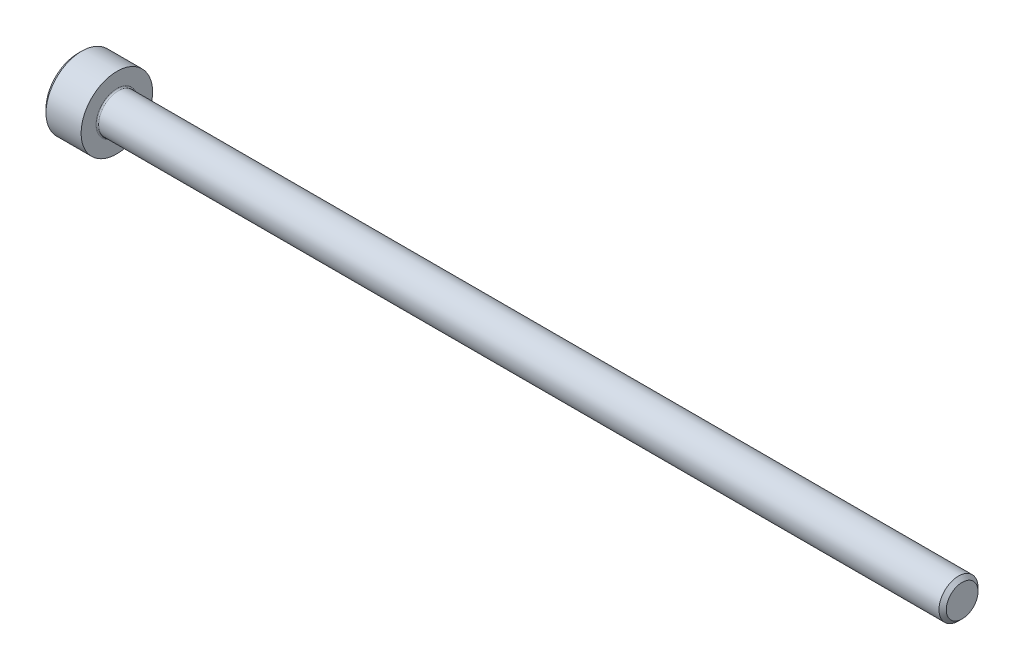
SolidWorks part; units mm, degrees
revolve "Base-Revolve" add sketch "BodySke"
sketch "BodySke" plane through (0, 0, 0) normal (0, 0, 1) x (1, 0, 0)
  line L0 (0, 0) -> (0, 2.45)
  line L1 (0.3, 2.75) -> (3, 2.75)
  line L2 (3, 2.75) -> (3, 1.5)
  line L3 (3, 1.5) -> (67.7195, 1.5)
  line L4 (68, 1.2195) -> (68, 0)
  line L5 (68, 0) -> (0, 0)
  line L6 (-31.75, 0) -> (127, 0) construction
  line L7 (0, 2.45) -> (0.3, 2.75)
  line L8 (68, 1.2195) -> (67.7195, 1.5)
  line L9 (0, -2.45) -> (0.3, -2.75) construction
  line L10 (68, -1.2195) -> (67.7195, -1.5) construction
  line L11 (3.5, 9.525) -> (3.5, 3.175) construction
  line L12 (50, 9.525) -> (50, 3.175) construction
  line L13 (18, 9.525) -> (18, 3.175) construction
  dimension "Diameter" = 3
  dimension "Head_ht" = 3
  dimension "Length" = 65
  dimension "Body_ch_ang" = 45
  dimension "Head_dia" = 5.5
  dimension "Head_ch_ang" = 45
  dimension "Minor_dia" = 2.439
  dimension "Advance" = 0.5
  dimension "Thread_nom" = 18
  dimension "Thread_length" = 50
  dimension "Head_ch_ht" = 0.3
cosmetic thread "ThreadCosmetic" [suppressed]
fillet "Fillet1" radius 0.1 1 edges at (3, 0, 1.5)
ref_plane "Plane1" through (0, 0, 0) normal (0, 0, 1) x (1, 0, 0)
ref_plane "Plane2" through (0, 0, 0) normal (0, 1, 0) x (1, 0, 0)
ref_plane "Plane3" through (0, 0, 0) normal (1, 0, 0) x (0, 0, -1)
sketch "Sketch2" plane through (0, 0, 0) normal (0, 0, 1) x (1, 0, 0)
  line L0 (0, 1.28) -> (1.3, 1.28)
  line L1 (1.3, 1.28) -> (2.039, 0)
  line L2 (-31.75, 0) -> (127, 0) construction
  line L3 (2.039, 0) -> (0, 0)
  line L4 (0, 0) -> (0, 1.28)
  line L5 (0, 2.45) -> (0, -2.45) construction
  line L6 (0, 0) -> (47.625, 0) construction
  line L7 (3, -2.75) -> (3, 2.75) construction
  dimension "D2" = 60
revolve "Hex-PreBroach" cut sketch "Sketch2" angle 360 about L6
sketch "Sketch3" plane through (0, 0, 0) normal (-1, 0, 0) x (0, 0.5, 0.866)
  line L0 (0.739, 1.28) -> (-0.739, 1.28)
  line L1 (-0.739, 1.28) -> (-1.478, 0)
  line L2 (0.739, 1.28) -> (1.478, 0)
  line L3 (0.739, -1.28) -> (1.478, 0)
  line L4 (0.739, -1.28) -> (-0.739, -1.28)
  line L5 (-0.739, -1.28) -> (-1.478, 0)
extrude "Hex" cut sketch "Sketch3" against normal blind 1.3
sketch "Sketch4" plane through (0, 0, 0) normal (-1, 0, 0) x (0, 0, 1)
  line L0 (0, 0) -> (1.4605, 0)
  line L1 (0, 0) -> (6.1484, 3.5498) construction
  line L2 (0, 0) -> (0.7302, 1.2648)
  line L3 (1.2009, 0.3267) -> (1.3933, 0.4378)
  line L4 (0.8834, 0.8767) -> (1.0758, 0.9877)
  arc A0 (1.2009, 0.3267) -> (0.8834, 0.8767) centre (0, 0) ccw
  arc A1 (1.4605, 0) -> (1.3933, 0.4378) centre (0, 0) ccw
  arc A2 (0.7302, 1.2648) -> (1.0758, 0.9877) centre (0, 0) cw
  dimension "D1" = 30
  dimension "D2" = 60
extrude "Spline" [suppressed] cut sketch "Sketch4" against normal blind 1.3
pattern_circular "CirPattern1" [suppressed] count 6 every 60
sketch "Sketch5" plane through (0, 0, 0) normal (0, 0, 1) x (1, 0, 0)
  line L0 (-31.75, 0) -> (127, 0) construction
  line L2 (0, 2.45) -> (0, -2.45) construction
  circle A0 centre (1.2, 0) radius 0.475
  dimension "Drilled_hole_dia" = 0.95
  dimension "Drilled_hole_loc" = 1.2
extrude "Hole" [suppressed] cut sketch "Sketch5" against normal through all and the other way through all
pattern_circular "Drilled-4" [suppressed] count 2 every 60
pattern_circular "Drilled-6" [suppressed] count 3 every 60
sketch "ThdSchSke" plane through (0, 0, 0) normal (0, 0, 1) x (1, 0, 0)
  line L0 (50, -1.2195) -> (49.8036, -1.5)
  line L1 (50, -1.2195) -> (50.1964, -1.5)
  line L2 (50.1964, -1.5) -> (50.1964, -1.875)
  line L3 (-3.175, 0) -> (5.1513, 0) construction
  line L5 (50.1964, -1.875) -> (49.8036, -1.875)
  line L6 (49.8036, -1.875) -> (49.8036, -1.5)
  line L7 (0, 2.45) -> (0, -2.45) construction
revolve "ThreadSchematic" [suppressed] cut sketch "ThdSchSke" angle 360 about L3
pattern_linear "ThdSchPat" [suppressed]
equation "\"D2@Sketch3\" = \"Hex_size@Sketch3\" / 2"
equation "\"D1@Sketch3\" = \"Hex_size@Sketch3\" / 2"
equation "\"D1@Sketch2\" = \"Hex_size@Sketch3\" / 2"
equation "\"D3@Sketch4\" = \"Spline_p_dim@Sketch4\" / 2"
equation "\"Thread_minor@ThreadCosmetic\"  =  \"Minor_dia@BodySke\""
equation "\"D2@CirPattern1\" = 360 / \"Num_teeth@CirPattern1\""
equation "\"Wall_thickness@Sketch2\" = \"Head_ht@BodySke\" - \"Key_eng@Hex\""
equation "\"Thread_length@ThreadCosmetic\" = ((sgn( (\"Length@BodySke\" - \"Advance@BodySke\" ) - \"Thread_nom@BodySke\" )-1)*( (\"Length@BodySke\" - \"Advance@BodySke\" ) - \"Thread_nom@BodySke\" ))/-2+ \"Thread_nom@BodySke\""
equation "\"Thread_minor@ThdSchSke\" = \"Minor_dia@BodySke\""
equation "\"Diameter@ThdSchSke\" = \"Diameter@BodySke\""
equation "\"Overcut@ThdSchSke\" = \"Diameter@BodySke\" * 1.25"
equation "\"Start@ThdSchSke\" = \"Head_ht@BodySke\" + \"Length@BodySke\" - \"Thread_length@ThreadCosmetic\"  '---Non-countersunk---"
equation "\"Num_threads@ThdSchPat\" = int( \"Thread_length@ThreadCosmetic\" / \"Advance@BodySke\" + 0.999 )  + 1"
equation "\"Advance@ThdSchPat\" = \"Thread_length@ThreadCosmetic\" /  (\"Num_threads@ThdSchPat\" - 1) 'relax it"
equation "\"Num_threads@ThdSchPat\" = \"Num_threads@ThdSchPat\" - sgn( \"Num_threads@ThdSchPat\" - 1) '---chamfered tips only---"
